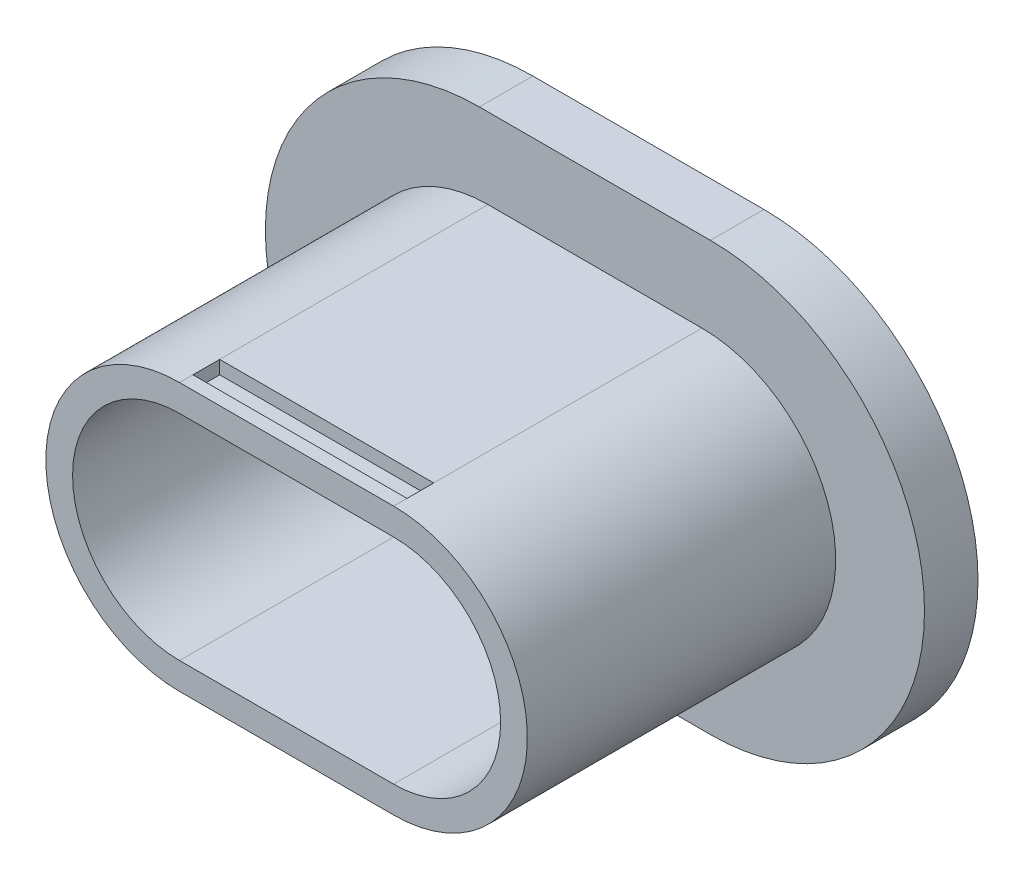
SolidWorks part; units mm, degrees
ref_plane "Front Plane" through (0, 0, 0) normal (0, 0, 1) x (1, 0, 0)
ref_plane "Top Plane" through (0, 0, 0) normal (0, 1, 0) x (1, 0, 0)
ref_plane "Right Plane" through (0, 0, 0) normal (1, 0, 0) x (0, 0, -1)
sketch "Sketch1" plane through (0, 0, 0) normal (0, 0, 1) x (1, 0, 0)
  line L0 (20.2442, 2.9156) -> (28.2442, 2.9156) construction
  line L1 (20.2442, 6.9156) -> (28.2442, 6.9156)
  line L2 (20.2442, -1.0844) -> (28.2442, -1.0844)
  line L3 (19.9257, 2.9156) -> (28.5627, 2.9156) construction
  line L4 (19.9257, 10.9156) -> (28.5627, 10.9156)
  line L5 (19.9257, -5.0844) -> (28.5627, -5.0844)
  line L6 (10.5583, 2.9156) -> (35.477, 2.9156) construction
  arc A0 (20.2442, 6.9156) -> (20.2442, -1.0844) centre (20.2442, 2.9156) ccw
  arc A1 (28.2442, -1.0844) -> (28.2442, 6.9156) centre (28.2442, 2.9156) ccw
  arc A2 (19.9257, 10.9156) -> (19.9257, -5.0844) centre (19.9257, 2.9156) ccw
  arc A3 (28.5627, -5.0844) -> (28.5627, 10.9156) centre (28.5627, 2.9156) ccw
  point P2 (24.2442, 2.9156)
  point P9 (24.2442, 2.9156)
  point P17 (16.2442, 2.9156)
  point P18 (32.2442, 2.9156)
  dimension "D1" = 8
  dimension "D2" = 8
  dimension "D3" = 0.3185
  dimension "D4" = 0.3185
  dimension "D5" = 4
  dimension "D6" = 16
extrude "BaseBoss-Extrude1" add sketch "Sketch1" along normal blind 2
sketch "Sketch2" plane through (0, 0, 2) normal (0, 0, 1) x (1, 0, 0)
  line L0 (20.2442, 2.9156) -> (28.2442, 2.9156) construction
  line L1 (20.2442, 7.9156) -> (28.2442, 7.9156)
  line L2 (20.2442, -2.0844) -> (28.2442, -2.0844)
  line L3 (13.2702, 2.9156) -> (37.4068, 2.9156) construction
  line L4 (28.2442, 6.9156) -> (20.2442, 6.9156) construction
  line L5 (20.2442, 2.9156) -> (28.2442, 2.9156) construction
  line L6 (20.2442, 6.9156) -> (28.2442, 6.9156)
  line L7 (20.2442, -1.0844) -> (28.2442, -1.0844)
  line L8 (20.2442, -1.0844) -> (28.2442, -1.0844) construction
  arc A0 (20.2442, 7.9156) -> (20.2442, -2.0844) centre (20.2442, 2.9156) ccw
  arc A1 (28.2442, -2.0844) -> (28.2442, 7.9156) centre (28.2442, 2.9156) ccw
  arc A2 (20.2442, 6.9156) -> (20.2442, -1.0844) centre (20.2442, 2.9156) ccw construction
  arc A3 (20.2442, 6.9156) -> (20.2442, -1.0844) centre (20.2442, 2.9156) ccw
  arc A4 (28.2442, -1.0844) -> (28.2442, 6.9156) centre (28.2442, 2.9156) ccw
  arc A5 (28.2442, -1.0844) -> (28.2442, 6.9156) centre (28.2442, 2.9156) ccw construction
  point P2 (24.2442, 2.9156)
  point P16 (24.2442, 2.9156)
  point P26 (15.2442, 2.9156)
  point P27 (33.2442, 2.9156)
  point P28 (16.2442, 2.9156)
  point P29 (32.2442, 2.9156)
  dimension "D2" = 1
  dimension "D3" = 1
  dimension "D4" = 8
  dimension "D5" = 18
  dimension "D1" = 1
  dimension "D6" = 10
extrude "Boss-Extrude2" add sketch "Sketch2" along normal blind 11.525 separate body
sketch "Sketch3" plane through (0, -2.0844, 0) normal (0, -1, 0) x (1, 0, 0)
  line L0 (20.2442, 13.525) -> (20.2442, 2) construction
  line L1 (20.2442, 13.025) -> (28.2442, 13.025)
  line L2 (20.2442, 13.025) -> (20.2442, 12.025)
  line L3 (20.2442, 12.025) -> (28.2442, 12.025)
  line L4 (28.2442, 13.025) -> (28.2442, 12.025)
  line L5 (28.2442, 13.525) -> (28.2442, 2) construction
  line L6 (20.2442, 13.525) -> (28.2442, 13.525) construction
  dimension "D1" = 0.5
  dimension "D2" = 1
extrude "Cut-Extrude1" cut sketch "Sketch3" against normal blind 0.5
sketch "Sketch4" plane through (0, 7.9156, 0) normal (0, 1, 0) x (1, 0, 0)
  line L0 (20.2442, -13.525) -> (20.2442, -2) construction
  line L1 (20.2442, -12.025) -> (28.2442, -12.025)
  line L2 (20.2442, -12.025) -> (20.2442, -13.025)
  line L3 (20.2442, -13.025) -> (28.2442, -13.025)
  line L4 (28.2442, -12.025) -> (28.2442, -13.025)
  line L5 (28.2442, -13.525) -> (28.2442, -2) construction
  line L6 (28.2442, -13.525) -> (20.2442, -13.525) construction
  dimension "D1" = 0.5
  dimension "D2" = 1
extrude "Cut-Extrude2" cut sketch "Sketch4" against normal blind 0.5
equation "\"HoleLength\"= 6mm"
equation "\"D1@Sketch1\"=\"HoleLength\" + \"HoleWidth\"/4"
equation "\"HoleWidth\"= 8mm"
equation "\"D2@Sketch1\"=\"HoleWidth\" "
equation "\"LipWidth\"= 2mm"
equation "\"D3@Sketch1\"=\"LipWidth\"/6.28"
equation "\"D4@Sketch1\"=\"LipWidth\"/6.28"
equation "\"D5@Sketch1\"=\"LipWidth\" + \"WallThickness\"*2"
equation "\"LipDepth\"= 2mm"
equation "\"HoleDepth\"= .25in + .125in + \"LipDepth\""
equation "\"D1@BaseBoss-Extrude1\" = \"LipDepth\""
equation "\"WallThickness\"= 1mm"
equation "\"D1@Boss-Extrude2\"=\"HoleDepth\""
equation "\"D1@Sketch3\"=\"LipDepth\"/4"
equation "\"D2@Sketch3\"=\"LipDepth\"/2"
equation "\"D1@Cut-Extrude1\"=\"WallThickness\"/2"
equation "\"D1@Sketch4\"=\"LipDepth\"/4"
equation "\"D2@Sketch4\"=\"LipDepth\"/2"
equation "\"D1@Cut-Extrude2\"=\"WallThickness\"/2"
equation "\"D3@Sketch2\"=\"WallThickness\""
equation "\"D1@Sketch2\"=\"WallThickness\""
equation "\"D2@Sketch2\"=\"WallThickness\""
